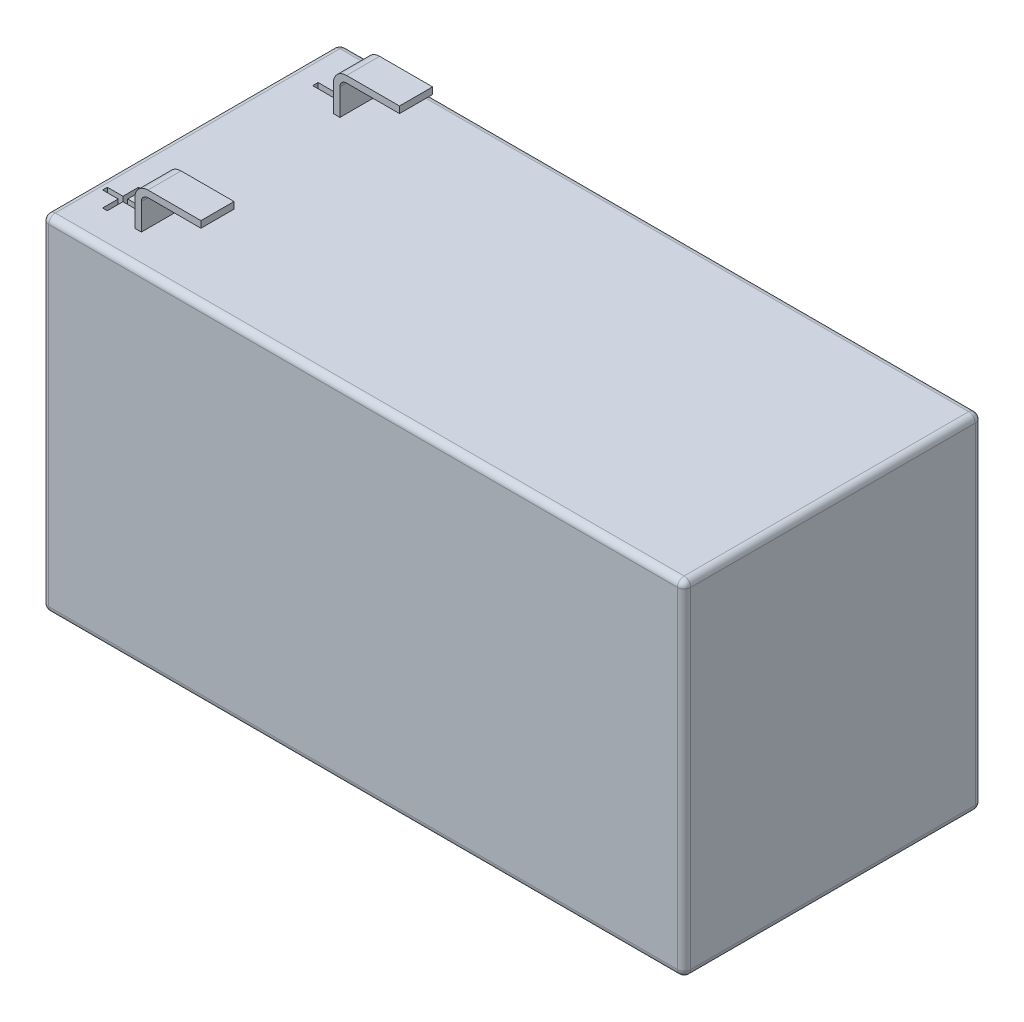
SolidWorks part; units mm, degrees
material "Anticorodal"
ref_plane "Piano frontale" through (0, 0, 0) normal (0, 0, 1) x (1, 0, 0)
ref_plane "Piano superiore" through (0, 0, 0) normal (0, 1, 0) x (1, 0, 0)
ref_plane "Piano destro" through (0, 0, 0) normal (1, 0, 0) x (0, 0, -1)
sketch "Schizzo1" plane through (0, 0, 0) normal (0, 0, 1) x (1, 0, 0)
  line L0 (24.75, 0) -> (-24.75, 0) construction
  line L1 (-48.5, 52) -> (48.5, 52)
  line L2 (-48.5, 52) -> (-48.5, 0)
  line L3 (-48.5, 0) -> (48.5, 0)
  line L4 (48.5, 52) -> (48.5, 0)
  line L5 (0, -24.75) -> (0, 24.75) construction
  dimension "D1" = 48.5
  dimension "D2" = 97
  dimension "D3" = 52
extrude "Estrusione1" add sketch "Schizzo1" along normal mid plane 45
fillet "Raccordo1" radius 1 12 edges at (48.5, 0, 0) (0, 0, -22.5) (48.5, 26, -22.5) (48.5, 26, 22.5) (0, 0, 22.5) (-48.5, 26, 22.5) (-48.5, 0, 0) (-48.5, 26, -22.5) (48.5, 52, 0) (0, 52, 22.5) (-48.5, 52, 0) (0, 52, -22.5)
sketch "Schizzo3" plane through (0, 0, 0) normal (0, 0, 1) x (1, 0, 0)
  line L0 (-38.5, 52) -> (-38.5, 56)
  line L1 (-47.5, 52) -> (47.5, 52) construction
  line L2 (-37.5, 57) -> (-29.5, 57)
  line L3 (-48.5, 1) -> (-48.5, 51) construction
  line L4 (-39.5, 52) -> (-39.5, 56)
  line L5 (-37.5, 58) -> (-29.5, 58)
  line L6 (-39.5, 52) -> (-38.5, 52)
  line L7 (-29.5, 58) -> (-29.5, 57)
  arc A0 (-37.5, 57) -> (-38.5, 56) centre (-37.5, 56) ccw
  arc A1 (-37.5, 58) -> (-39.5, 56) centre (-37.5, 56) ccw
  point P9 (-38.5, 57)
  dimension "D4" = 1
  dimension "D1" = 5
  dimension "D2" = 10
  dimension "D3" = 9
  dimension "D5" = 1
extrude "Estrusione2" add sketch "Schizzo3" along normal mid plane 35
sketch "Schizzo4" plane through (0, 52, 0) normal (0, 1, 0) x (-1, 0, 0)
  line L0 (29.5, 17.5) -> (37.5, 17.5) construction
  line L1 (44.2584, -12.5) -> (10.2747, -12.5)
  line L2 (44.2584, -12.5) -> (44.2584, 12.5)
  line L3 (44.2584, 12.5) -> (10.2747, 12.5)
  line L4 (10.2747, -12.5) -> (10.2747, 12.5)
  line L5 (29.5, -17.5) -> (37.5, -17.5) construction
  dimension "D1" = 5
  dimension "D2" = 5
extrude "Taglio-Estrusione2" cut sketch "Schizzo4" along normal blind 35
sketch "Schizzo5" plane through (0, 52, 0) normal (0, 1, 0) x (-1, 0, 0)
  text T0 "+" font "Century Gothic" height 8
  text T1 "-" font "Century Gothic" height 8
extrude "Taglio-Estrusione3" cut sketch "Schizzo5" against normal blind 5
